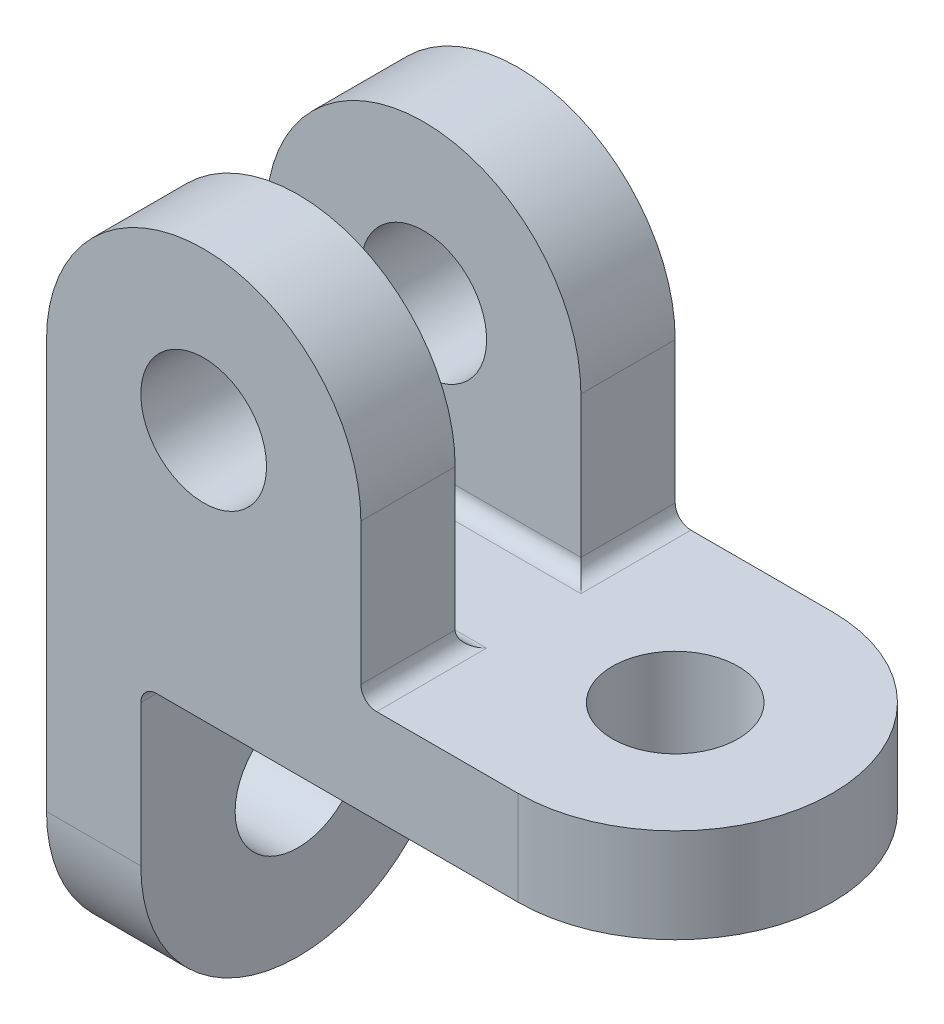
SolidWorks part; units mm, degrees
ref_plane "Front Plane" through (0, 0, 0) normal (0, 0, 1) x (1, 0, 0)
ref_plane "Top Plane" through (0, 0, 0) normal (0, 1, 0) x (1, 0, 0)
ref_plane "Right Plane" through (0, 0, 0) normal (1, 0, 0) x (0, 0, -1)
sketch "Sketch1" plane through (0, 0, 0) normal (0, 1, 0) x (1, 0, 0)
  line L0 (0, 62.4772) -> (0, -22.4772) construction
  line L1 (-46.3222, 0) -> (-13.6778, 0) construction
  line L2 (-30, 20) -> (-30, -20)
  line L3 (-30, -20) -> (30, -20)
  line L5 (30, 20) -> (-30, 20)
  line L6 (-13.6778, 0) -> (40.2128, 0) construction
  arc A0 (30, 20) -> (30, -20) centre (30, 0) cw
  point P7 (-30, 0)
  point P10 (0, 20)
  dimension "D1" = 60
  dimension "D2" = 60
  dimension "D3" = 40
extrude "Boss-Extrude1" add sketch "Sketch1" along normal blind 12
sketch "Sketch2" plane through (0, 12, 0) normal (0, 1, 0) x (1, 0, 0)
  circle A0 centre (30, 0) radius 8
  arc A1 (30, -20) -> (30, 20) centre (30, 0) ccw construction
  point P2 (0, 0)
  point P6 (50, 0)
  dimension "D1" = 16
extrude "Cut-Extrude1" cut sketch "Sketch2" against normal through all
sketch "Sketch3" plane through (0, 0, 20) normal (0, 0, 1) x (1, 0, 0)
  line L0 (-30, 32) -> (-30, 12)
  line L1 (-30, 12) -> (10, 12)
  line L2 (-30, 12) -> (30, 12) construction
  line L3 (10, 12) -> (10, 32)
  line L4 (-30, 32) -> (10, 32) construction
  arc A0 (-30, 32) -> (10, 32) centre (-10, 32) cw
  circle A1 centre (-10, 32) radius 8
  dimension "D4" = 16
  dimension "D1" = 20
  dimension "D2" = 20
  dimension "D3" = 40
extrude "Boss-Extrude2" add sketch "Sketch3" against normal blind 12
sketch "Sketch4" plane through (0, 0, -20) normal (0, 0, -1) x (-1, 0, 0)
  line L0 (-10, 32) -> (-10, 12)
  line L1 (-10, 12) -> (30, 12)
  line L2 (30, 12) -> (30, 32)
  line L3 (-10, 32) -> (30, 32) construction
  arc A0 (-10, 32) -> (30, 32) centre (10, 32) cw
  circle A1 centre (10, 32) radius 8
  dimension "D1" = 16
extrude "Boss-Extrude3" add sketch "Sketch4" against normal blind 12
sketch "Sketch5" plane through (-30, 0, 0) normal (-1, 0, 0) x (0, 0, 1)
  line L0 (-20, -20) -> (-20, 0)
  line L1 (-20, 0) -> (20, 0)
  line L2 (20, 0) -> (20, -20)
  line L3 (-20, -20) -> (20, -20) construction
  arc A0 (-20, -20) -> (20, -20) centre (0, -20) ccw
  circle A1 centre (0, -20) radius 8
  dimension "D3" = 16
  dimension "D1" = 20
  dimension "D2" = 20
extrude "Boss-Extrude4" add sketch "Sketch5" against normal blind 12
fillet "Fillet1" radius 2 5 edges at (-10, 12, 8) (-10, 12, -8) (10, 12, -14) (10, 12, 14) (-18, 0, 0)
